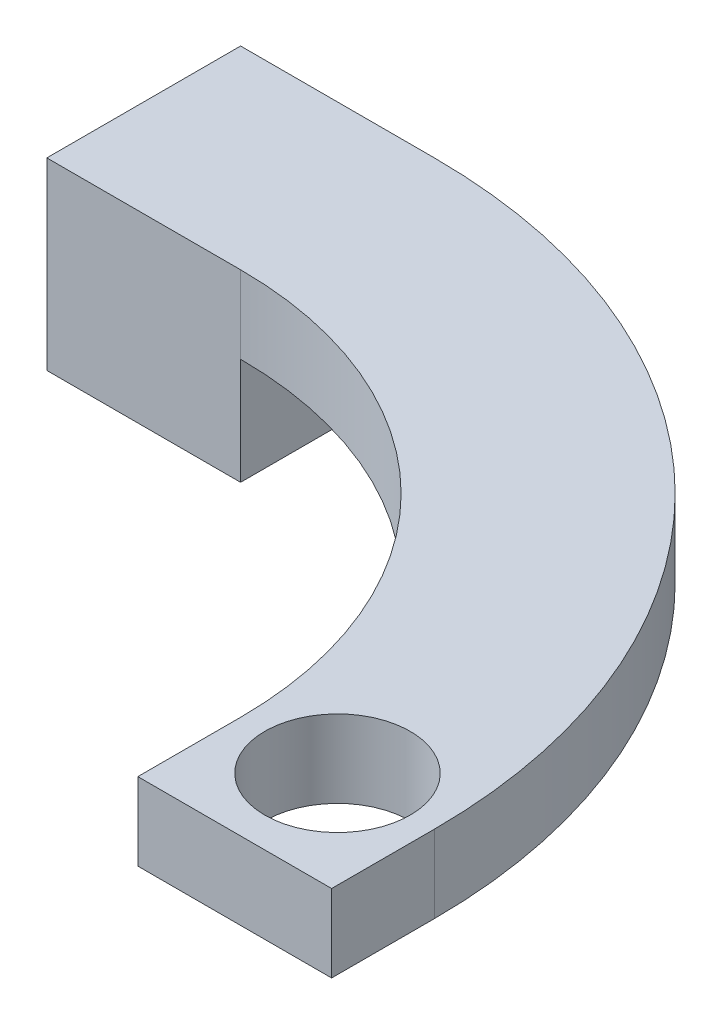
SolidWorks part; units mm, degrees
ref_plane "Front Plane" through (0, 0, 0) normal (0, 0, 1) x (1, 0, 0)
ref_plane "Top Plane" through (0, 0, 0) normal (0, 1, 0) x (1, 0, 0)
ref_plane "Right Plane" through (0, 0, 0) normal (1, 0, 0) x (0, 0, -1)
sketch "Sketch1" plane through (0, 0, 0) normal (0, 1, 0) x (1, 0, 0)
  line L1 (0, 0) -> (69.6617, 0) construction
  line L2 (10.6066, 10.6066) -> (80.1265, 10.6066) construction
  line L3 (50.6066, 10.6066) -> (50.6066, 0)
  line L4 (0, 0) -> (20.4482, 20.4482) construction
  line L5 (50.6066, 0) -> (70.6066, 0)
  line L6 (10.6066, 10.6066) -> (10.6066, 73.3904) construction
  line L7 (70.6066, 0) -> (70.6066, 10.6066)
  line L8 (10.6066, 70.6066) -> (-9.3934, 70.6066)
  line L9 (-9.3934, 70.6066) -> (-9.3934, 50.6066)
  line L10 (-9.3934, 50.6066) -> (10.6066, 50.6066)
  circle A2 centre (60.6066, 10.6066) radius 7.5
  circle A3 centre (10.6066, 10.6066) radius 1.5
  arc A4 (50.6066, 10.6066) -> (10.6066, 50.6066) centre (10.6066, 10.6066) ccw
  arc A5 (70.6066, 10.6066) -> (10.6066, 70.6066) centre (10.6066, 10.6066) ccw
  dimension "D1" = 40
  dimension "D3" = 45
  dimension "D5" = 3
  dimension "D8" = 15
  dimension "D2" = 60
  dimension "D4" = 15
  dimension "D6" = 50
  dimension "D7" = 20
extrude "Boss-Extrude1" add sketch "Sketch1" along normal blind 8
sketch "Croquis6" plane through (0, 0, 0) normal (0, -1, 0) x (1, 0, 0)
  line L1 (-9.3934, -50.6066) -> (10.6066, -50.6066)
  line L2 (-9.3934, -50.6066) -> (-9.3934, -70.6066)
  line L3 (-9.3934, -70.6066) -> (10.6066, -70.6066)
  line L4 (10.6066, -50.6066) -> (10.6066, -70.6066)
extrude "Saliente-Extruir5" add sketch "Croquis6" along normal blind 11
sketch "Croquis7" plane through (0, -11, 0) normal (0, -1, 0) x (1, 0, 0)
  line L0 (-9.3934, -60.6066) -> (10.6066, -60.6066) construction
  line L1 (-9.3934, -50.6066) -> (-9.3934, -70.6066) construction
  line L2 (10.6066, -70.6066) -> (10.6066, -50.6066) construction
  line L3 (0.6066, -50.6066) -> (0.6066, -70.6066) construction
  line L4 (10.6066, -50.6066) -> (-9.3934, -50.6066) construction
  line L5 (-9.3934, -70.6066) -> (10.6066, -70.6066) construction
  circle A0 centre (-5.3934, -60.6066) radius 1.5
  circle A1 centre (6.6066, -60.6066) radius 1.5
  circle A2 centre (0.6066, -66.6066) radius 1.5
  circle A3 centre (0.6066, -54.6066) radius 1.5
  point P20 (0.6066, -60.6066)
  dimension "D1" = 3
  dimension "D2" = 12
  dimension "D3" = 12
  dimension "D4" = 10
extrude "Cortar-Extruir1" cut sketch "Croquis7" against normal blind 10
